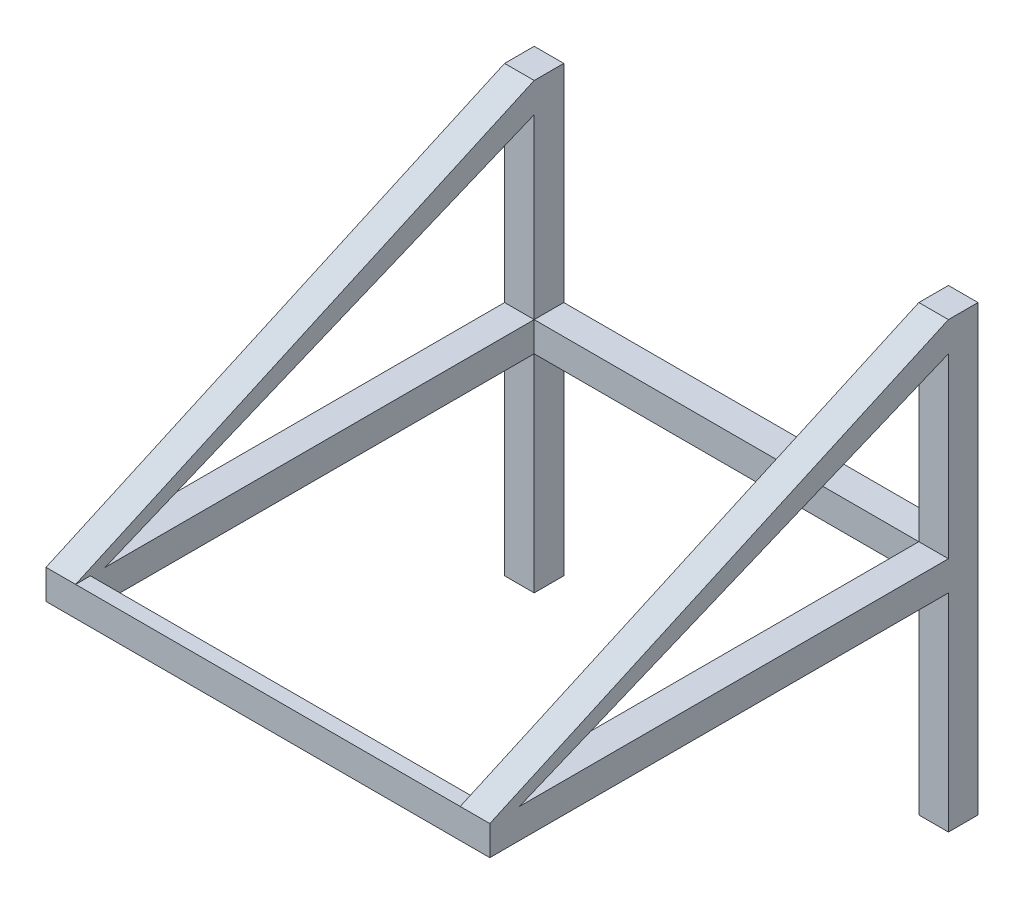
SolidWorks part; units mm, degrees
ref_plane "Front Plane" through (0, 0, 0) normal (0, 0, 1) x (1, 0, 0)
ref_plane "Top Plane" through (0, 0, 0) normal (0, 1, 0) x (1, 0, 0)
ref_plane "Right Plane" through (0, 0, 0) normal (1, 0, 0) x (0, 0, -1)
sketch "Sketch1" plane through (0, 0, 0) normal (0, 0, 1) x (1, 0, 0)
  line L1 (0, 0) -> (1524, 0)
  line L2 (0, 0) -> (0, 1524)
  line L3 (0, 1524) -> (1524, 1524)
  line L4 (1524, 0) -> (1524, 1524)
  dimension "D1" = 1524
  dimension "D2" = 1524
extrude "Boss-Extrude1" add sketch "Sketch1" along normal blind 101.6
sketch "Sketch2" plane through (0, 0, 101.6) normal (0, 0, 1) x (1, 0, 0)
  line L1 (101.6, 1524) -> (1422.4, 1524)
  line L2 (101.6, 1524) -> (101.6, 812.8)
  line L3 (101.6, 812.8) -> (1422.4, 812.8)
  line L4 (1422.4, 1524) -> (1422.4, 812.8)
  line L5 (0, 0) -> (1524, 0) construction
  line L6 (1422.4, 0) -> (101.6, 0)
  line L7 (1422.4, 0) -> (1422.4, 711.2)
  line L8 (1422.4, 711.2) -> (101.6, 711.2)
  line L9 (101.6, 0) -> (101.6, 711.2)
  line L10 (0, 0) -> (101.6, 0) construction
  line L11 (1422.4, 0) -> (1524, 0) construction
  line L12 (1524, 1524) -> (0, 1524) construction
  dimension "D1" = 101.6
  dimension "D2" = 101.6
  dimension "D3" = 101.6
extrude "Cut-Extrude1" cut sketch "Sketch2" against normal through all
sketch "Sketch3" plane through (0, 0, 101.6) normal (0, 0, 1) x (1, 0, 0)
  line L0 (0, 1524) -> (0, 0) construction
  line L1 (101.6, 812.8) -> (0, 812.8)
  line L2 (101.6, 812.8) -> (101.6, 711.2)
  line L3 (101.6, 711.2) -> (0, 711.2)
  line L4 (0, 812.8) -> (0, 711.2)
  line L5 (1524, 0) -> (1524, 1524) construction
  line L6 (1422.4, 812.8) -> (1524, 812.8)
  line L7 (1422.4, 812.8) -> (1422.4, 711.2)
  line L8 (1422.4, 711.2) -> (1524, 711.2)
  line L9 (1524, 812.8) -> (1524, 711.2)
  line L10 (1422.4, 711.2) -> (101.6, 711.2) construction
extrude "Boss-Extrude2" add sketch "Sketch3" along normal blind 1524
sketch "Sketch4" plane through (0, 0, 1625.6) normal (0, 0, 1) x (1, 0, 0)
  line L1 (1524, 812.8) -> (0, 812.8)
  line L2 (1524, 812.8) -> (1524, 711.2)
  line L3 (1524, 711.2) -> (0, 711.2)
  line L4 (0, 812.8) -> (0, 711.2)
extrude "Boss-Extrude3" add sketch "Sketch4" along normal blind 50.8
sketch "Sketch5" plane through (0, 0, 101.6) normal (0, 0, 1) x (1, 0, 0)
  line L0 (1524, 812.8) -> (1524, 1524) construction
  line L1 (1422.4, 1524) -> (1524, 1524)
  line L2 (1422.4, 1524) -> (1422.4, 1422.4)
  line L3 (1422.4, 1422.4) -> (1524, 1422.4)
  line L4 (1524, 1524) -> (1524, 1422.4)
  dimension "D1" = 101.6
sketch "Sketch6" plane through (0, 812.8, 0) normal (0, 1, 0) x (1, 0, 0)
  line L0 (1422.4, -1625.6) -> (1422.4, -101.6) construction
  line L1 (1524, -1676.4) -> (1422.4, -1676.4)
  line L2 (1524, -1676.4) -> (1524, -1574.8)
  line L3 (1524, -1574.8) -> (1422.4, -1574.8)
  line L4 (1422.4, -1676.4) -> (1422.4, -1574.8)
  dimension "D1" = 101.6
loft "Loft1" add profiles "Sketch6", "Sketch5"
sketch "Sketch13" plane through (0, 0, 101.6) normal (0, 0, 1) x (1, 0, 0)
  line L0 (101.6, 1524) -> (101.6, 812.8) construction
  line L1 (0, 1524) -> (101.6, 1524)
  line L2 (0, 1524) -> (0, 1422.4)
  line L3 (0, 1422.4) -> (101.6, 1422.4)
  line L4 (101.6, 1524) -> (101.6, 1422.4)
  dimension "D1" = 101.6
sketch "Sketch14" plane through (0, 812.8, 0) normal (0, 1, 0) x (1, 0, 0)
  line L0 (101.6, -1625.6) -> (101.6, -101.6) construction
  line L1 (0, -1676.4) -> (101.6, -1676.4)
  line L2 (0, -1676.4) -> (0, -1574.8)
  line L3 (0, -1574.8) -> (101.6, -1574.8)
  line L4 (101.6, -1676.4) -> (101.6, -1574.8)
  dimension "D1" = 101.6
loft "Loft2" add profiles "Sketch14", "Sketch13"
